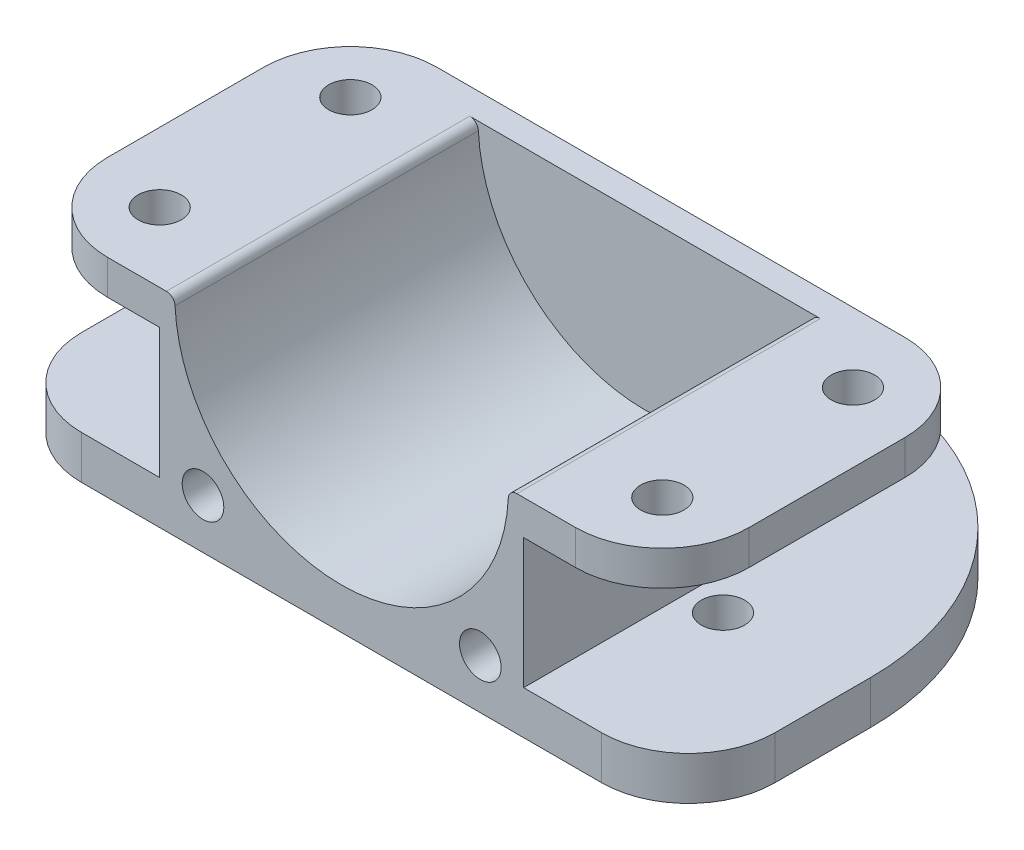
SolidWorks part; units mm, degrees
ref_plane "Front Plane" through (0, 0, 0) normal (0, 0, 1) x (1, 0, 0)
ref_plane "Top Plane" through (0, 0, 0) normal (0, 1, 0) x (1, 0, 0)
ref_plane "Right Plane" through (0, 0, 0) normal (1, 0, 0) x (0, 0, -1)
sketch "Sketch1" plane through (0, 0, 0) normal (0, 0, 1) x (1, 0, 0)
  line L1 (-21, -24) -> (21, -24)
  line L2 (-21, -24) -> (-21, 24)
  line L3 (-21, 24) -> (21, 24)
  line L4 (21, -24) -> (21, 24)
  line L5 (-21, -24) -> (21, 24) construction
  line L6 (-21, 24) -> (21, -24) construction
  circle A0 centre (0, 0) radius 19.25
  circle A1 centre (-16, 18.2857) radius 2.4
  circle A2 centre (16, 18.2857) radius 2.4
  circle A3 centre (16, -18.2857) radius 2.4
  circle A4 centre (-16, -18.2857) radius 2.4
  point P0 (0, 0)
  dimension "D3" = 38.5
  dimension "D4" = 4.8
  dimension "D1" = 48
  dimension "D2" = 42
  dimension "D5" = 5
extrude "Boss-Extrude1" add sketch "Sketch1" against normal blind 35
sketch "Sketch4" plane through (0, 0, 0) normal (0, 0, 1) x (1, 0, 0)
  line L1 (-21, -24) -> (-40, -24)
  line L2 (-21, -24) -> (-21, -19)
  line L3 (-21, -19) -> (-40, -19)
  line L4 (-40, -24) -> (-40, -19)
  line L5 (21, -24) -> (40, -24)
  line L6 (21, -24) -> (21, -19)
  line L7 (21, -19) -> (40, -19)
  line L8 (40, -24) -> (40, -19)
  dimension "D1" = 5
  dimension "D2" = 80
extrude "Boss-Extrude3" add sketch "Sketch4" against normal up to surface (35 mm away) up to face at (-13.6, -18.2857, -35)
sketch "Sketch5" plane through (0, -19, 0) normal (0, 1, 0) x (1, 0, 0)
  line L0 (-25, 19) -> (-40, 35) construction
  line L1 (25, 19) -> (40, 35) construction
  line L2 (-21, 35) -> (-40, 35) construction
  circle A0 centre (-25, 19) radius 2.5
  circle A1 centre (25, 19) radius 2.5
  dimension "D1" = 5
  dimension "D2" = 50
  dimension "D3" = 16
extrude "Cut-Extrude1" cut sketch "Sketch5" against normal up to next
sketch "Sketch6" plane through (0, 0, -35) normal (0, 0, -1) x (-1, 0, 0)
  line L8 (-21, 24) -> (-21, -19)
  line L9 (-21, -19) -> (-40, -19)
  line L10 (-40, -19) -> (-40, -24)
  line L11 (-40, -24) -> (40, -24)
  line L12 (40, -24) -> (40, -19)
  line L13 (40, -19) -> (21, -19)
  line L14 (21, -19) -> (21, 24)
  line L15 (21, 24) -> (-21, 24)
  line L16 (-21, 24) -> (-21, -19)
  line L17 (-21, -19) -> (-40, -19)
  line L18 (-40, -19) -> (-40, -24)
  line L19 (-40, -24) -> (40, -24)
  line L20 (40, -24) -> (40, -19)
  line L21 (40, -19) -> (21, -19)
  line L22 (21, -19) -> (21, 24)
  line L23 (21, 24) -> (-21, 24)
  dimension "D1" = 0
extrude "Boss-Extrude4" add sketch "Sketch6" along normal blind 3
sketch "Sketch7" plane through (0, 0, 0) normal (0, 0, 1) x (1, 0, 0)
  line L0 (-21, 24) -> (-21, -19) construction
  line L1 (-21, 0) -> (21, 0)
  line L2 (-21, 0) -> (-21, 24)
  line L3 (-21, 24) -> (21, 24)
  line L4 (21, 0) -> (21, 24)
  dimension "D1" = 0
extrude "Cut-Extrude2" cut sketch "Sketch7" against normal up to next
fillet "Fillet1" radius 1 2 edges at (19.25, 0, -17.5) (-19.25, 0, -17.5)
sketch "Sketch8" plane through (0, -24, 0) normal (0, -1, 0) x (1, 0, 0)
  line L0 (40, -38) -> (-40, -38) construction
  line L1 (-40, -38) -> (40, -38)
  line L2 (-40, -38) -> (-40, -51)
  line L3 (-40, -51) -> (40, -51)
  line L4 (40, -38) -> (40, -51)
  line L5 (-40, -38) -> (40, -51) construction
  line L6 (-40, -51) -> (40, -38) construction
  point P0 (0, -44.5)
  dimension "D2" = 13
extrude "Boss-Extrude5" add sketch "Sketch8" against normal up to surface (5 mm away) up to face at (25, -19, -16.5)
sketch "Sketch10" plane through (0, -19, 0) normal (0, 1, 0) x (1, 0, 0)
  line L0 (-15, 43) -> (-40, 51) construction
  line L1 (15, 43) -> (40, 51) construction
  line L2 (21, 38) -> (-21, 38) construction
  circle A0 centre (-15, 43) radius 2.5
  circle A1 centre (15, 43) radius 2.5
  dimension "D1" = 30
  dimension "D2" = 5
  dimension "D3" = 5
extrude "Cut-Extrude4" cut sketch "Sketch10" against normal up to next
fillet "Fillet5" radius 30 2 edges at (-40, -21.5, -51) (40, -21.5, -51)
fillet "Fillet6" radius 10 2 edges at (-40, -21.5, 0) (40, -21.5, 0)
sketch "Sketch12" plane through (-21, 0, 0) normal (-1, 0, 0) x (0, 0, 1)
  line L0 (-38, -19) -> (-38, 0) construction
  line L1 (0, 0) -> (-38, 0)
  line L2 (0, 0) -> (0, -4)
  line L3 (0, -4) -> (-38, -4)
  line L4 (-38, 0) -> (-38, -4)
  dimension "D1" = 4
extrude "Boss-Extrude6" add sketch "Sketch12" along normal blind 16
sketch "Sketch13" plane through (0, 0, 0) normal (0, 1, 0) x (1, 0, 0)
  line L0 (-37, 0) -> (-20.2253, 0) construction
  line L2 (-37, 0) -> (-37, 38) construction
  circle A0 centre (-29, 8) radius 2.5
  circle A1 centre (-29, 30) radius 2.5
  dimension "D2" = 5
  dimension "D3" = 8
  dimension "D4" = 8
  dimension "D1" = 22
extrude "Cut-Extrude5" cut sketch "Sketch13" against normal up to next
fillet "Fillet7" radius 10 2 edges at (-37, -2, -38) (-37, -2, 0)
mirror "Mirror1" about plane through (0, 0, 0) normal (1, 0, 0) of "Boss-Extrude6", "Cut-Extrude5", "Fillet7"
